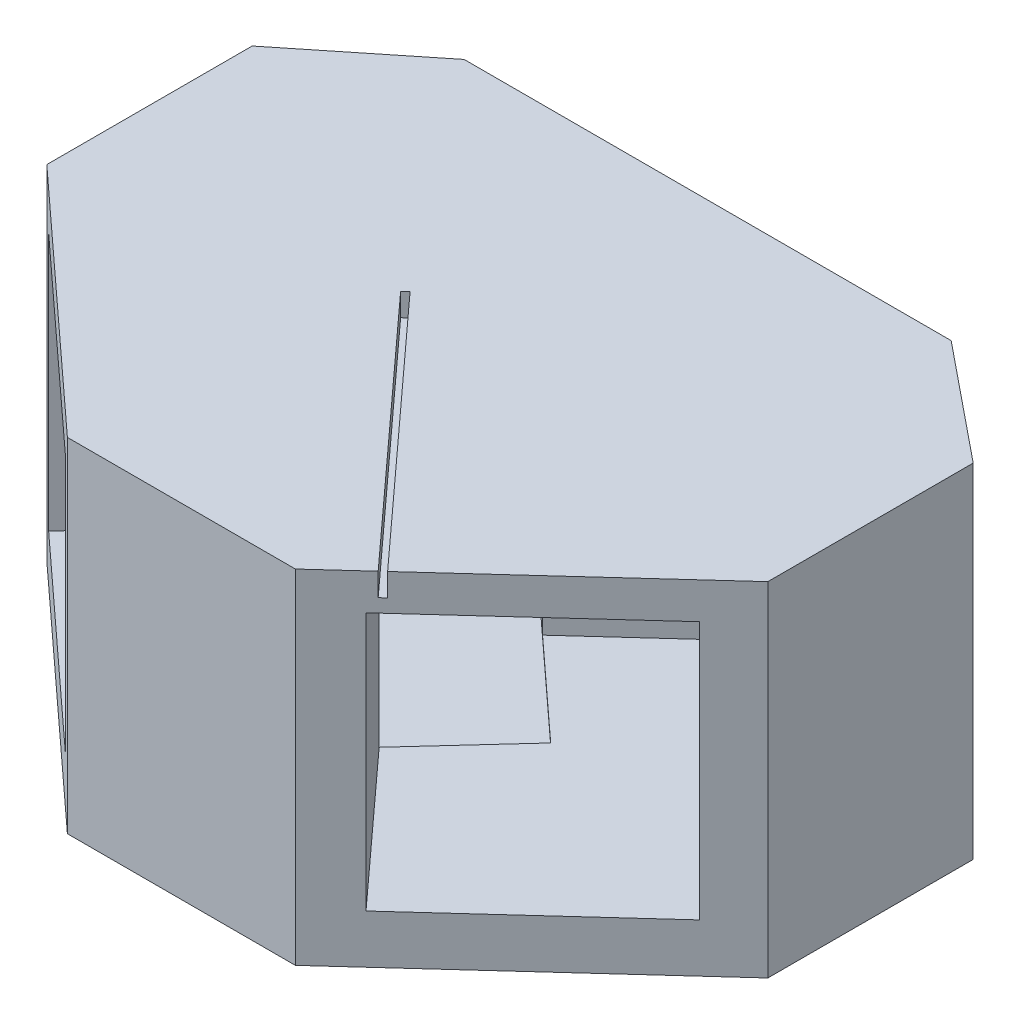
SolidWorks part; units mm, degrees
ref_plane "Front Plane" through (0, 0, 0) normal (0, 0, 1) x (1, 0, 0)
ref_plane "Top Plane" through (0, 0, 0) normal (0, 1, 0) x (1, 0, 0)
ref_plane "Right Plane" through (0, 0, 0) normal (1, 0, 0) x (0, 0, -1)
sketch "Sketch2" plane through (0, 0, 0) normal (0, 1, 0) x (1, 0, 0)
  line L0 (-826.129, -44.3965) -> (-786.0352, -12.2337)
  line L1 (-786.0352, -12.2337) -> (-620.0352, -12.2337)
  line L2 (-620.0352, -12.2337) -> (-580.1291, -44.6292)
  line L3 (-580.1291, -44.6292) -> (-580.1291, -114.6292)
  line L4 (-580.1291, -114.6292) -> (-664.3847, -191.421)
  line L5 (-664.3847, -191.421) -> (-742.086, -191.421)
  line L7 (-826.129, -44.3965) -> (-826.129, -114.3965)
  line L8 (-742.086, -191.421) -> (-826.129, -114.3965)
  point P2 (-703.2354, -191.421)
  dimension "D1" = 70
  dimension "D2" = 70
  dimension "D3" = 114
  dimension "D4" = 114
  dimension "D5" = 179.1873
  dimension "D6" = 166
  dimension "D7" = 51.4
  dimension "D8" = 51.4
  dimension "D9" = 246
extrude "Boss-Extrude3" add sketch "Sketch2" along normal blind 117
sketch "Sketch3" plane through (-206.1671, 0, -226.2055) normal (0.6736, 0, 0.7391) x (0.7391, 0, -0.6736)
  line L1 (-597.7179, 132.9908) -> (-599.9999, 132.9908)
  line L2 (-597.7179, 132.9908) -> (-597.7179, 109.1929)
  line L3 (-597.7179, 109.1929) -> (-599.9999, 109.1929)
  line L4 (-599.9999, 132.9908) -> (-599.9999, 109.1929)
  line L5 (-602.9339, 104.6289) -> (-522.4121, 104.6289)
  line L6 (-602.9339, 104.6289) -> (-602.9339, 16.6091)
  line L7 (-602.9339, 16.6091) -> (-522.4121, 16.6091)
  line L8 (-522.4121, 104.6289) -> (-522.4121, 16.6091)
extrude "Cut-Extrude1" cut sketch "Sketch3" against normal blind 117
sketch "Sketch4" plane through (-434.1161, 0, 473.6724) normal (-0.6757, 0, 0.7372) x (0.7372, 0, 0.6757)
  line L1 (-521.5836, 103.9629) -> (-427.073, 103.9629)
  line L2 (-521.5836, 103.9629) -> (-521.5836, 15.9702)
  line L3 (-521.5836, 15.9702) -> (-427.073, 15.9702)
  line L4 (-427.073, 103.9629) -> (-427.073, 15.9702)
extrude "Cut-Extrude2" cut sketch "Sketch4" against normal blind 117
